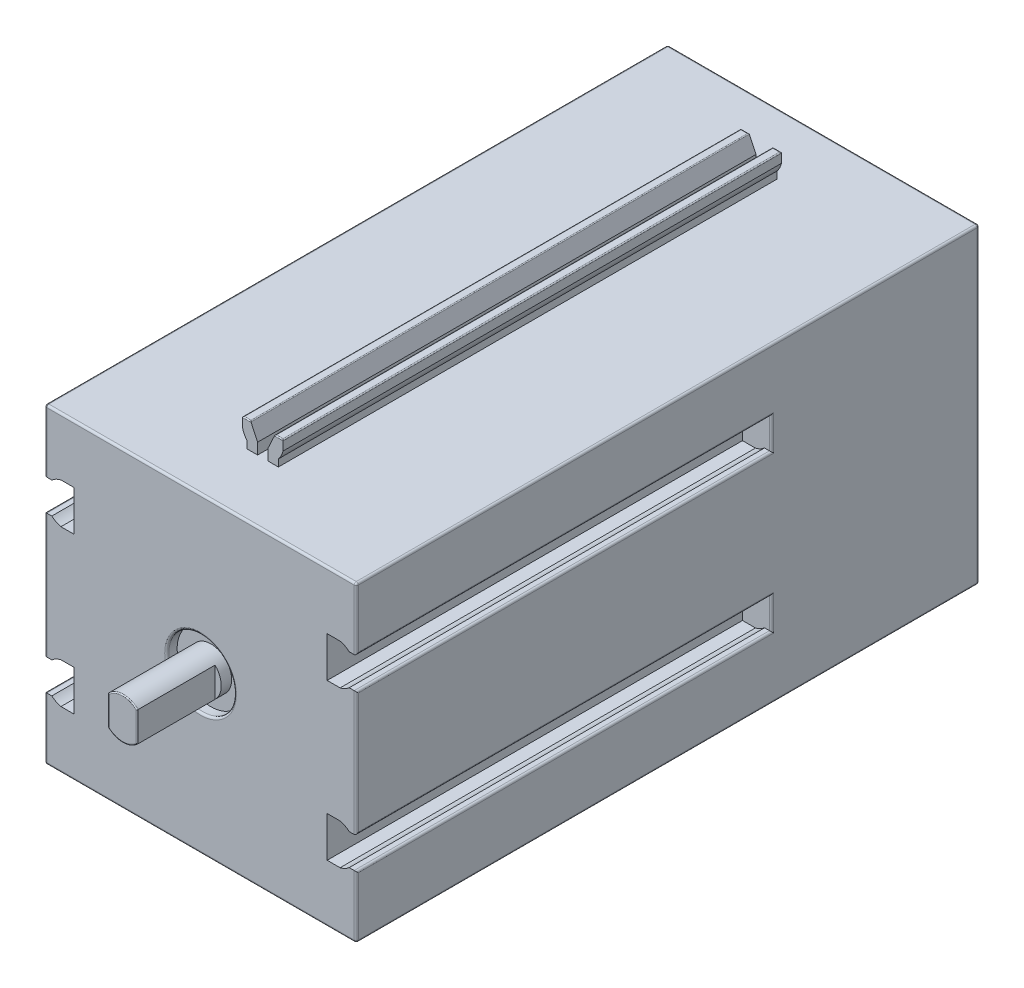
SolidWorks part; units mm, degrees
ref_plane "前视基准面" through (0, 0, 0) normal (0, 0, 1) x (1, 0, 0)
ref_plane "上视基准面" through (0, 0, 0) normal (0, 1, 0) x (1, 0, 0)
ref_plane "右视基准面" through (0, 0, 0) normal (1, 0, 0) x (0, 0, -1)
sketch "草图1" plane through (0, 0, 0) normal (0, 0, 1) x (1, 0, 0)
  line L1 (-15, 0) -> (15, 0)
  line L2 (-15, 0) -> (-15, 30)
  line L3 (-15, 30) -> (15, 30)
  line L4 (15, 0) -> (15, 30)
extrude "凸台-拉伸1" add sketch "草图1" against normal blind 60
sketch "草图2" plane through (0, 0, -60) normal (0, 0, -1) x (-1, 0, 0)
  line L0 (-9, 0.6771) -> (-9, 0)
  line L1 (15, 0) -> (-15, 0) construction
  line L2 (0, -2.0675) -> (0, 3.9748) construction
  line L3 (-6, 0.6771) -> (-6, 0)
  line L4 (-6, 0) -> (-9, 0)
  line L5 (-9.45, 2.8) -> (-5.55, 2.8)
  line L6 (-9.45, 2.8) -> (-9.45, 1.5556)
  line L7 (5.55, 2.8) -> (5.55, 1.5556)
  line L8 (-5.55, 2.8) -> (-5.55, 1.5556)
  line L9 (9.45, 2.8) -> (9.45, 1.5556)
  line L10 (9.45, 2.8) -> (5.55, 2.8)
  line L11 (6, 0) -> (9, 0)
  line L12 (6, 0.6771) -> (6, 0)
  line L13 (9, 0.6771) -> (9, 0)
  arc A0 (9.45, 1.5556) -> (9, 0.6771) centre (7.5, 2) cw
  arc A1 (-6, 0.6771) -> (-5.55, 1.5556) centre (-7.5, 2) ccw
  arc A2 (-9.45, 1.5556) -> (-9, 0.6771) centre (-7.5, 2) ccw
  arc A3 (6, 0.6771) -> (5.55, 1.5556) centre (7.5, 2) cw
extrude "切除-拉伸1" cut sketch "草图2" against normal blind 54.5
sketch "草图3" plane through (0, 0, -60) normal (0, 0, -1) x (-1, 0, 0)
  line L0 (-14.3229, 9) -> (-15, 9)
  line L1 (-15, 0) -> (-15, 30) construction
  line L2 (-15, 6) -> (-14.3229, 6)
  line L3 (-12.2, 9.45) -> (-12.2, 5.55)
  line L4 (-15, 9) -> (-15, 6)
  line L5 (-12.2, 5.55) -> (-13.4444, 5.55)
  line L6 (-12.2, 9.45) -> (-13.4444, 9.45)
  line L8 (-12.2, 20.55) -> (-13.4444, 20.55)
  line L9 (-12.2, 24.45) -> (-13.4444, 24.45)
  line L10 (-15, 21) -> (-15, 24)
  line L11 (-12.2, 20.55) -> (-12.2, 24.45)
  line L12 (-15, 24) -> (-14.3229, 24)
  line L13 (-14.3229, 21) -> (-15, 21)
  line L15 (14.3229, 21) -> (15, 21)
  line L16 (15, 24) -> (14.3229, 24)
  line L17 (12.2, 20.55) -> (12.2, 24.45)
  line L18 (15, 21) -> (15, 24)
  line L19 (12.2, 24.45) -> (13.4444, 24.45)
  line L20 (12.2, 20.55) -> (13.4444, 20.55)
  line L21 (12.2, 9.45) -> (13.4444, 9.45)
  line L22 (12.2, 5.55) -> (13.4444, 5.55)
  line L23 (15, 9) -> (15, 6)
  line L24 (12.2, 9.45) -> (12.2, 5.55)
  line L25 (15, 6) -> (14.3229, 6)
  line L26 (14.3229, 9) -> (15, 9)
  arc A0 (-14.3229, 6) -> (-13.4444, 5.55) centre (-13, 7.5) ccw
  arc A1 (-13.4444, 9.45) -> (-14.3229, 9) centre (-13, 7.5) ccw
  arc A2 (-13.4444, 20.55) -> (-14.3229, 21) centre (-13, 22.5) cw
  arc A3 (-14.3229, 24) -> (-13.4444, 24.45) centre (-13, 22.5) cw
  arc A4 (14.3229, 24) -> (13.4444, 24.45) centre (13, 22.5) ccw
  arc A5 (13.4444, 20.55) -> (14.3229, 21) centre (13, 22.5) ccw
  arc A6 (13.4444, 9.45) -> (14.3229, 9) centre (13, 7.5) cw
  arc A7 (14.3229, 6) -> (13.4444, 5.55) centre (13, 7.5) cw
extrude "切除-拉伸2" cut sketch "草图3" along normal blind 40 from offset 60 offset against normal yes
sketch "草图5" plane through (0, 0, -60) normal (0, 0, -1) x (-1, 0, 0)
  line L0 (-1.5, 30.6771) -> (-1.5, 30)
  line L1 (-15, 30) -> (15, 30) construction
  line L2 (1.5, 30) -> (1.5, 30.6771)
  line L3 (-1.95, 32.5) -> (-1.1658, 32.5)
  line L4 (-1.95, 32.5) -> (-1.95, 31.5556)
  line L5 (1.95, 32.5) -> (1.95, 31.5556)
  line L6 (-1.5, 30) -> (-0.5, 30)
  line L7 (-0.5, 30) -> (-0.5, 31.0723)
  line L8 (0.5, 30) -> (0.5, 31.0723)
  line L9 (-0.5, 31.0723) -> (-1.1658, 32.5)
  line L10 (0.5, 31.0723) -> (1.1658, 32.5)
  line L11 (1.1658, 32.5) -> (1.95, 32.5)
  line L12 (0.5, 30) -> (1.5, 30)
  arc A1 (-1.95, 31.5556) -> (-1.5, 30.6771) centre (0, 32) ccw
  arc A2 (1.5, 30.6771) -> (1.95, 31.5556) centre (0, 32) ccw
extrude "凸台-拉伸2" add sketch "草图5" against normal blind 48 from offset 6 offset against normal yes
fillet "圆角1" radius 0.1 8 edges at (-1.1658, 32.5, -30) (-1.5579, 32.5, -6) (-1.95, 32.5, -30) (-1.5579, 32.5, -54) (1.95, 32.5, -30) (1.5579, 32.5, -6) (1.1658, 32.5, -30) (1.5579, 32.5, -54)
sketch "草图6" plane through (0, 0, 0) normal (0, 0, 1) x (1, 0, 0)
  circle A0 centre (0, 15) radius 3.25
extrude "切除-拉伸3" cut sketch "草图6" against normal blind 1
sketch "草图7" plane through (0, 0, -1) normal (0, 0, 1) x (1, 0, 0)
  circle A0 centre (0, 15) radius 2
extrude "凸台-拉伸3" add sketch "草图7" along normal blind 8.5
sketch "草图9" plane through (0, 0, 7.5) normal (0, 0, 1) x (1, 0, 0)
  line L2 (-1.4, 16.4283) -> (-1.4, 13.5717)
  line L4 (1.4, 16.4283) -> (1.4, 13.5717)
  arc A3 (-1.4, 16.4283) -> (-1.4, 13.5717) centre (0, 15) ccw
  arc A4 (1.4, 13.5717) -> (1.4, 16.4283) centre (0, 15) ccw
extrude "切除-拉伸5" cut sketch "草图9" against normal up to surface (7.5 mm away) up to face at (3.25, 15, 0)
sketch "草图10" plane through (0, 0, -60) normal (0, 0, -1) x (-1, 0, 0)
  circle A0 centre (-10.5, 25.5) radius 1.25
  circle A1 centre (10.5, 25.5) radius 1.25
extrude "切除-拉伸6" cut sketch "草图10" against normal blind 5
sketch "草图11" plane through (0, 0, -60) normal (0, 0, -1) x (-1, 0, 0)
  line L0 (2.5, 24) -> (4, 24)
  line L1 (-4, 27) -> (4, 27)
  line L2 (-4, 27) -> (-4, 24)
  line L3 (-4, 24) -> (-2.5, 24)
  line L4 (4, 27) -> (4, 24)
  line L6 (-2.5, 24) -> (-2.5, 25)
  line L7 (-2.5, 25) -> (2.5, 25)
  line L8 (2.5, 24) -> (2.5, 25)
extrude "切除-拉伸7" cut sketch "草图11" against normal blind 5
fillet "圆角2" radius 0.2 37 edges at (-12, 0, -60) (0, 0, 0) (12, 0, -60) (9, 0, -32.75) (7.5, 0, -5.5) (6, 0, -32.75) (0, 0, -60) (-6, 0, -32.75) (-7.5, 0, -5.5) (-9, 0, -32.75) (-15, 0, -30) (-15, 15, -60) (-15, 30, -30) (-15, 27, 0) (-15, 24, -20) (-15, 22.5, -40) (-15, 21, -20) (-15, 15, 0) (-15, 9, -20) (-15, 7.5, -40) (-15, 6, -20) (-15, 3, 0) (15, 30, -30) (15, 15, -60) (15, 0, -30) (15, 3, 0) (15, 6, -20) (15, 7.5, -40) (15, 9, -20) (15, 15, 0) (15, 21, -20) (15, 22.5, -40) (15, 24, -20) (15, 27, 0) (0, 30, -60) (3.25, 15, 0) (0, 30, 0)
fillet "圆角3" radius 0.1 4 edges at (0, 13, 7.5) (0, 17, 7.5) (1.4, 15, 7.5) (-1.4, 15, 7.5)
